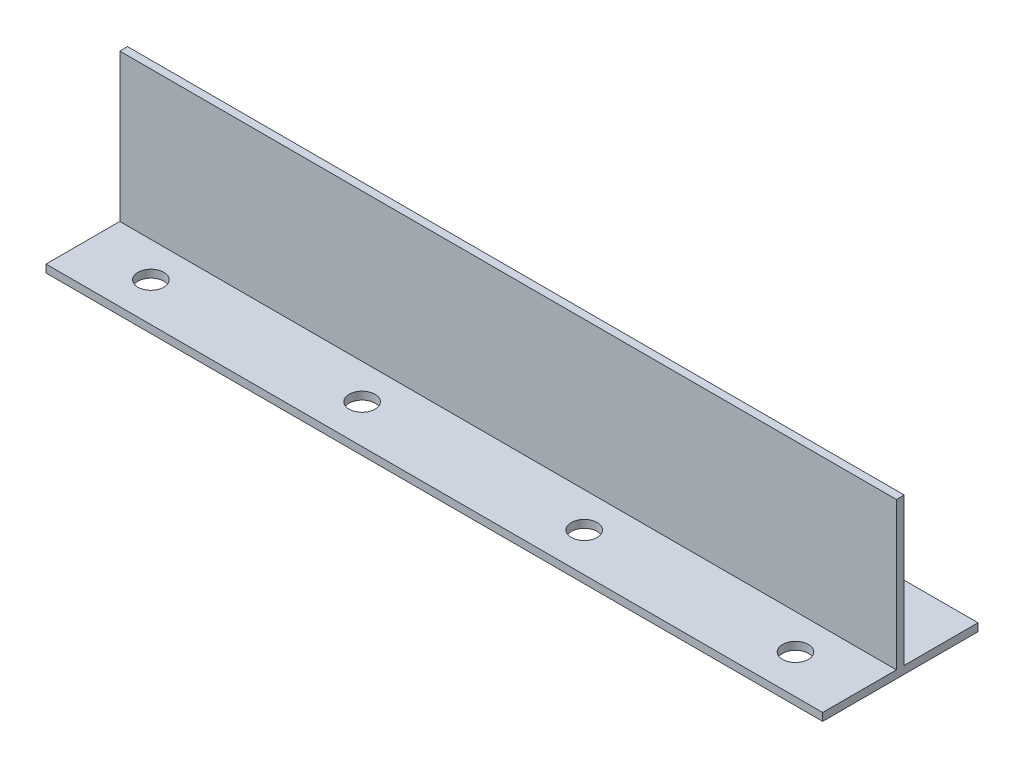
SolidWorks part; units mm, degrees
material "6061-T4 (SS)"
ref_plane "Front" through (0, 0, 0) normal (0, 0, 1) x (1, 0, 0)
ref_plane "Top" through (0, 0, 0) normal (0, 1, 0) x (1, 0, 0)
ref_plane "Right" through (0, 0, 0) normal (1, 0, 0) x (0, 0, -1)
sketch "Sketch1" plane through (0, 0, 0) normal (1, 0, 0) x (0, 0, -1)
  line L0 (-14.25, 0) -> (15.75, 0)
  line L1 (15.75, 0) -> (15.75, 1.5)
  line L2 (15.75, 1.5) -> (1.5, 1.5)
  line L3 (1.5, 1.5) -> (1.5, 30)
  line L4 (1.5, 30) -> (0, 30)
  line L5 (0, 30) -> (0, 1.5)
  line L6 (0, 1.5) -> (-14.25, 1.5)
  line L7 (-14.25, 1.5) -> (-14.25, 0)
  dimension "D1" = 1.5
  dimension "D2" = 30
  dimension "D3" = 30
extrude "Boss-Extrude1" add sketch "Sketch1" along normal blind 150
sketch "Sketch2" plane through (0, 1.5, 0) normal (0, 1, 0) x (1, 0, 0)
  line L0 (75, 15.75) -> (75, -14.25) construction
  line L1 (150, 15.75) -> (0, 15.75) construction
  line L2 (150, -14.25) -> (0, -14.25) construction
  line L3 (12.75, 8.25) -> (12.75, -6.75) construction
  line L4 (137.25, 8.25) -> (137.25, -6.75) construction
  line L5 (0, 1.5) -> (0, 0) construction
  line L6 (0, 15.75) -> (0, 1.5) construction
  circle A0 centre (12.75, -6.75) radius 2.5
  circle A1 centre (12.75, 8.25) radius 2.5
  circle A2 centre (53.55, 8.25) radius 2.5
  circle A3 centre (53.55, -6.75) radius 2.5
  circle A4 centre (96.45, -6.75) radius 2.5
  circle A5 centre (96.45, 8.25) radius 2.5
  circle A6 centre (137.25, 8.25) radius 2.5
  circle A7 centre (137.25, -6.75) radius 2.5
  point P10 (12.75, 0.75)
  point P27 (0, 0.75)
  dimension "D3" = 5
  dimension "D2" = 15
  dimension "D4" = 40.8
  dimension "D1" = 12.75
extrude "Cut-Extrude1" cut sketch "Sketch2" against normal through all
sketch "Sketch3" plane through (0, 1.5, 0) normal (0, 1, 0) x (1, 0, 0)
  line L0 (75, 15.75) -> (75, -14.25) construction
  line L1 (150, 15.75) -> (0, 15.75) construction
  line L2 (150, -14.25) -> (0, -14.25) construction
  line L3 (0, 0) -> (0, -14.25) construction
  circle A0 centre (11, -7.5) radius 2.5
  circle A1 centre (20, -7.5) radius 2.5
  circle A2 centre (48.3, -7.5) radius 2.5
  circle A3 centre (57.3, -7.5) radius 2.5
  circle A4 centre (92.7, -7.5) radius 2.5
  circle A5 centre (101.7, -7.5) radius 2.5
  circle A6 centre (130, -7.5) radius 2.5
  circle A7 centre (139, -7.5) radius 2.5
  dimension "D3" = 5
  dimension "D1" = 7.5
  dimension "D2" = 9
  dimension "D4" = 9
  dimension "D6" = 11
  dimension "D5" = 46.3
extrude "Cut-Extrude2" [suppressed] cut sketch "Sketch3" against normal through all
equation "\"length\"=30"
equation "\"D2@Sketch1\"=\"length\""
equation "\"D3@Sketch1\"=\"length\""
equation "\"D2@Sketch2\"=\"length\"/2"
equation "\"D1@Sketch3\"=\"length\"/4"
